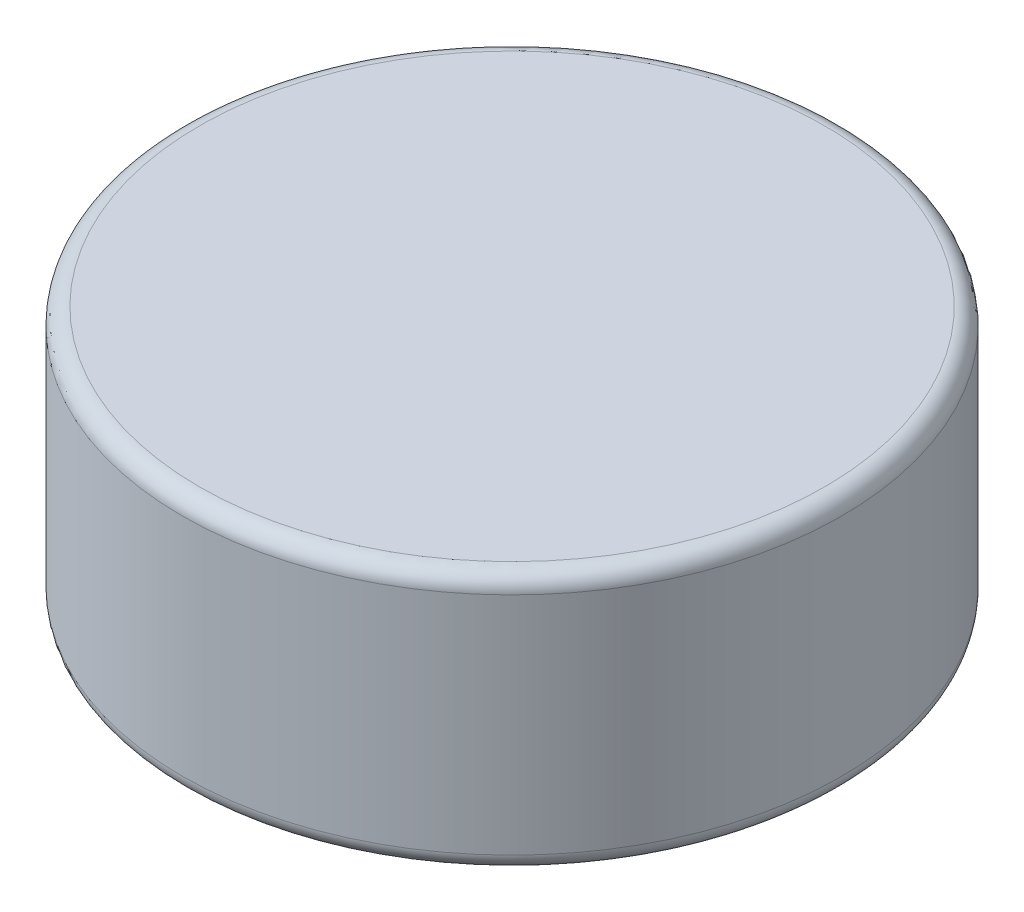
SolidWorks part; units mm, degrees
ref_plane "Спереди" through (0, 0, 0) normal (0, 0, 1) x (1, 0, 0)
ref_plane "Сверху" through (0, 0, 0) normal (0, 1, 0) x (1, 0, 0)
ref_plane "Справа" through (0, 0, 0) normal (1, 0, 0) x (0, 0, -1)
sketch "Эскиз1" plane through (0, 0, 0) normal (0, 1, 0) x (1, 0, 0)
  circle A0 centre (0, 0) radius 58.5
  dimension "D1" = 117
extrude "Бобышка-Вытянуть1" add sketch "Эскиз1" along normal blind 46
fillet "Скругление1" radius 3 2 edges at (0, 46, 58.5) (0, 0, 58.5)
